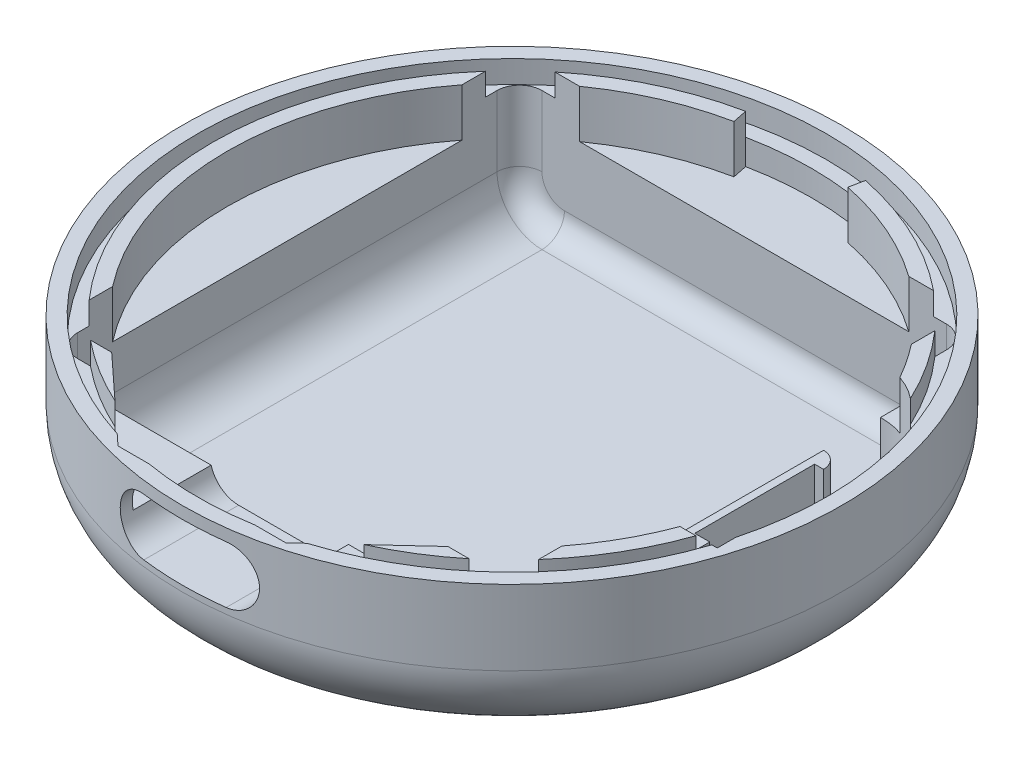
SolidWorks part; units mm, degrees
ref_plane "Front Plane" through (0, 0, 0) normal (0, 0, 1) x (1, 0, 0)
ref_plane "Top Plane" through (0, 0, 0) normal (0, 1, 0) x (1, 0, 0)
ref_plane "Right Plane" through (0, 0, 0) normal (1, 0, 0) x (0, 0, -1)
sketch "Sketch1" plane through (0, 0, 0) normal (0, 1, 0) x (1, 0, 0)
  circle A0 centre (0, 0) radius 22
  dimension "D1" = 44
extrude "Boss-Extrude1" add sketch "Sketch1" along normal blind 10
sketch "Sketch2" plane through (0, 10, 0) normal (0, 1, 0) x (1, 0, 0)
  line L0 (-12.8997, -13.9498) -> (-5.6, -20.7)
  line L1 (-5.6, -20.7) -> (5.6, -20.7)
  line L2 (5.6, -20.7) -> (12.8997, -13.9498)
  line L3 (0, 0) -> (0, -20.7) construction
  line L4 (4, 19.5959) -> (3.8, 18.6161)
  line L5 (-4, 19.5959) -> (-3.8, 18.6161)
  line L6 (3.8, 18.6161) -> (0, 0) construction
  line L7 (0, 0) -> (-3.8, 18.6161) construction
  line L8 (0, 19) -> (0, 20) construction
  line L9 (0, 0) -> (0, 19) construction
  arc A0 (-3.8, 18.6161) -> (3.8, 18.6161) centre (0, 0) ccw
  arc A1 (4, 19.5959) -> (-4, 19.5959) centre (0, 0) ccw
  arc A2 (0, 19) -> (-3.8, 18.6161) centre (0, 0) ccw construction
  arc A3 (3.8, 18.6161) -> (0, 19) centre (0, 0) ccw construction
  dimension "D1" = 38
  dimension "D5" = 1
  dimension "D2" = 11.2
  dimension "D3" = 20.7
  dimension "D4" = 8
extrude "Cut-Extrude1" cut sketch "Sketch2" against normal blind 3.2 contours L4 A1 L5 A0 | A0 L0 L1 L2
sketch "Sketch3" plane through (0, 6.8, 0) normal (0, 1, 0) x (1, 0, 0)
  line L0 (-15, -15.5) -> (15, 15.5) construction
  line L1 (-15, 15.5) -> (15, 15.5)
  line L2 (-15, 15.5) -> (-15, -15.5)
  line L3 (-15, -15.5) -> (15, -15.5)
  line L4 (15, 15.5) -> (15, -15.5)
  dimension "D1" = 31
  dimension "D2" = 30
extrude "Cut-Extrude2" cut sketch "Sketch3" against normal blind 6 and the other way through all
sketch "Sketch5" plane through (0, 0, 20.7) normal (0, 0, -1) x (-1, 0, 0)
  line L0 (-2.75, 7.3) -> (2.75, 7.3) construction
  line L1 (-2.75, 9.2) -> (2.75, 9.2)
  line L2 (-2.75, 5.4) -> (2.75, 5.4)
  line L3 (0, 7.3) -> (0, 10) construction
  line L4 (5.6, 10) -> (-5.6, 10) construction
  arc A0 (-2.75, 9.2) -> (-2.75, 5.4) centre (-2.75, 7.3) ccw
  arc A1 (2.75, 5.4) -> (2.75, 9.2) centre (2.75, 7.3) ccw
  point P2 (0, 7.3)
  point P7 (-4.65, 7.3)
  point P8 (4.65, 7.3)
  dimension "D1" = 9.3
  dimension "D2" = 3.8
  dimension "D3" = 0.8
extrude "Cut-Extrude3" cut sketch "Sketch5" against normal through all and the other way blind 6
fillet "Fillet1" radius 3 2 edges at (-15, 0.8, 0) (15, 0.8, 0)
fillet "Fillet2" radius 1.5 10 edges at (-15, 6.9, 15.5) (-14.1213, 1.6787, 15.5) (15, 6.9, 15.5) (14.1213, 1.6787, 15.5) (15, 6.9, -15.5) (14.1213, 1.6787, -15.5) (-15, 6.9, -15.5) (-14.1213, 1.6787, -15.5) (0, 0.8, 15.5) (0, 0.8, -15.5)
fillet "Fillet3" radius 5 1 edges at (0, 0, 22)
sketch "Sketch6" plane through (0, 6.8, 0) normal (0, 1, 0) x (1, 0, 0)
  line L0 (15, 14) -> (15, -14) construction
  line L14 (15.5, 0) -> (15, 0) construction
  line L17 (16.5, -4.3) -> (19.5, -4.3)
  line L18 (15, 5.8) -> (15, 9.6)
  line L19 (19.5, -4.3) -> (19.5, -3.3)
  line L20 (20.5, -3.3) -> (19.5, -3.3)
  line L21 (20.5, -4.3) -> (20.5, -3.3)
  line L22 (20.5, -4.3) -> (19.5, -4.3)
  line L23 (16.5, -4.3) -> (16.5, -3.3)
  line L24 (15.5, -3.3) -> (16.5, -3.3)
  line L25 (15.5, -4.3) -> (15.5, -3.3)
  line L26 (15.5, -4.3) -> (16.5, -4.3)
  line L27 (20.5, -7.3) -> (20.5, 4.7)
  line L28 (15.5, 4.7) -> (20.5, 4.7)
  line L29 (15.5, -7.3) -> (15.5, 4.7)
  line L30 (15.5, -7.3) -> (20.5, -7.3)
  arc A2 (15, 9.6) -> (19.9, 4.7) centre (15, 4.7) cw
  arc A3 (15, 5.8) -> (16.1, 4.7) centre (15, 4.7) cw
extrude "Cut-Extrude4" cut sketch "Sketch6" against normal blind 4 and the other way through all contours L29 L24 L23 L17 L19 L20 L27 L28 | L18 A3 L28 A2
sketch "Sketch11" plane through (0, 0, 4.3) normal (0, 0, 1) x (1, 0, 0)
  line L1 (15.7, 5.1) -> (15.7, 10)
  line L2 (15.7, 10) -> (20.3, 10)
  line L3 (20.3, 10) -> (20.3, 5.1)
  line L6 (16.5, 2.8) -> (19.5, 2.8) construction
  line L7 (22, 10) -> (-22, 10) construction
  arc A0 (15.7, 5.1) -> (20.3, 5.1) centre (18, 5.1) ccw
  arc A1 (20.3, 5.1) -> (15.7, 5.1) centre (18, 5.1) ccw construction
  point P4 (18, 2.8)
  point P12 (0, 0)
  dimension "D1" = 4.6
extrude "Cut-Extrude6" cut sketch "Sketch11" along normal blind 2.3
sketch "Sketch10" plane through (0, 10, 0) normal (0, 1, 0) x (1, 0, 0)
  line L0 (19.5, -4.3) -> (19.5323, -4.3)
  line L3 (19.5, -3.3) -> (19.7259, -3.3)
  line L6 (19.5, -3.3) -> (19.5, -4.3)
  line L7 (20.3, -4.3) -> (19.5, -4.3) construction
  circle A0 centre (0, 0) radius 21
  arc A1 (19.5323, -4.3) -> (19.7259, -3.3) centre (0, 0) ccw construction
  circle A2 centre (0, 0) radius 22 construction
  arc A3 (19.7259, -3.3) -> (19.5323, -4.3) centre (0, 0) ccw
  point P3 (0, 0)
  point P9 (19.7413, 3.2063)
  point P15 (17.9194, -2.6717)
  point P17 (19.5, 3.3)
  point P18 (0, 0)
  dimension "D1" = 1
  dimension "D2" = 1
extrude "Cut-Extrude5" cut sketch "Sketch10" against normal blind 1.5
